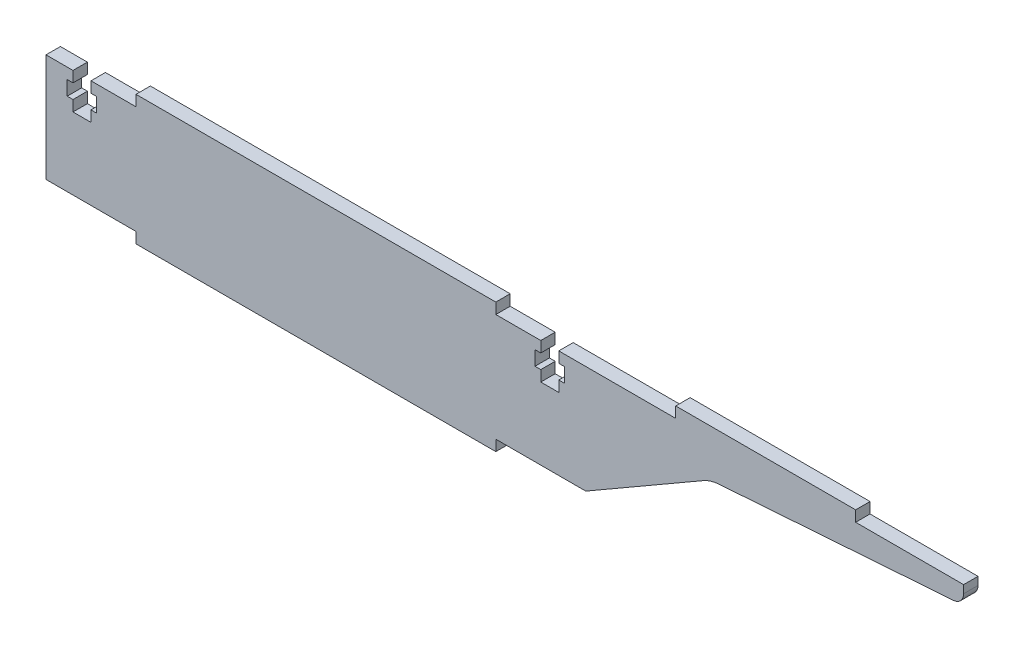
SolidWorks part; units mm, degrees
ref_plane "Front Plane" through (0, 0, 0) normal (0, 0, 1) x (1, 0, 0)
ref_plane "Top Plane" through (0, 0, 0) normal (0, 1, 0) x (1, 0, 0)
ref_plane "Right Plane" through (0, 0, 0) normal (1, 0, 0) x (0, 0, -1)
sketch "Sketch1" plane through (0, 0, 0) normal (0, 0, 1) x (1, 0, 0)
  line L1 (75, -15) -> (-75, -15)
  line L2 (75, -15) -> (75, 15)
  line L3 (75, 15) -> (-75, 15)
  line L4 (-75, -15) -> (-75, 15)
  line L5 (75, -15) -> (-75, 15) construction
  line L6 (75, 15) -> (-75, -15) construction
  line L7 (50, -18) -> (-50, -18)
  line L8 (50, -18) -> (50, -12)
  line L9 (50, -12) -> (-50, -12)
  line L10 (-50, -18) -> (-50, -12)
  line L11 (50, -18) -> (-50, -12) construction
  line L12 (50, -12) -> (-50, -18) construction
  line L13 (50, 12) -> (-50, 12)
  line L14 (50, 12) -> (50, 18)
  line L15 (50, 18) -> (-50, 18)
  line L16 (-50, 12) -> (-50, 18)
  line L17 (50, 12) -> (-50, 18) construction
  line L18 (50, 18) -> (-50, 12) construction
  point P0 (0, 0)
  point P6 (0, -15)
  point P11 (0, 15)
  dimension "D1" = 150
  dimension "D2" = 30
  dimension "D3" = 6
  dimension "D4" = 100
  dimension "D5" = 6
extrude "Boss-Extrude1" add sketch "Sketch1" along normal blind 4 contours L1 L10 L9 L8 L2 L3 L4 | L10 L7 L8 L1 | L10 L1 L8 L9 | L16 L3 L14 L15 | L16 L13 L14 L3
sketch "Sketch2" plane through (0, 0, 4) normal (0, 0, 1) x (1, 0, 0)
  line L1 (-67.5, 25) -> (-62.5, 25)
  line L2 (-67.5, 25) -> (-67.5, 5)
  line L3 (-67.5, 5) -> (-62.5, 5)
  line L4 (-62.5, 25) -> (-62.5, 5)
  line L5 (-67.5, 25) -> (-62.5, 5) construction
  line L6 (-67.5, 5) -> (-62.5, 25) construction
  line L8 (-60.9, 8) -> (-69.1, 8)
  line L9 (-60.9, 8) -> (-60.9, 12)
  line L10 (-60.9, 12) -> (-69.1, 12)
  line L11 (-69.1, 8) -> (-69.1, 12)
  line L12 (-60.9, 8) -> (-69.1, 12) construction
  line L13 (-60.9, 12) -> (-69.1, 8) construction
  point P0 (-65, 15)
  point P7 (-65, 10)
  dimension "D1" = 5
  dimension "D2" = 20
  dimension "D3" = 8.2
  dimension "D4" = 0
  dimension "D5" = 4
  dimension "D6" = 3
  dimension "D7" = 65
extrude "Cut-Extrude1" cut sketch "Sketch2" against normal blind 10 contours L4 L3 L2 L1 | L10 L11 L8 L9
mirror "Mirror1" about plane through (0, 0, 0) normal (1, 0, 0) of "Cut-Extrude1"
sketch "Sketch3" plane through (0, 0, 4) normal (0, 0, 1) x (1, 0, 0)
  line L0 (75, -15) -> (107.6468, 3.8486)
  line L1 (75, -15) -> (75, 15) construction
  line L2 (53.5141, 15) -> (155.2942, 15) construction
  line L3 (75, -15) -> (75, 15)
  line L4 (75, 15) -> (180, 15)
  line L5 (247.6295, 15) -> (292.9259, 15) construction
  line L6 (180, 15) -> (180, 12.7944)
  line L7 (177.2127, 9.8019) -> (111.9379, 5.1632)
  line L9 (100, 15) -> (150, 15)
  line L10 (100, 15) -> (100, 18)
  line L11 (100, 18) -> (150, 18)
  line L12 (150, 15) -> (150, 18)
  arc A0 (111.9379, 5.1632) -> (107.6468, 3.8486) centre (112.6468, -4.8116) ccw
  arc A1 (180, 12.7944) -> (177.2127, 9.8019) centre (177, 12.7944) cw
  point P15 (109.641, 5)
  point P22 (125, 18)
  line M27 (75, -15) -> (75, 15)
  dimension "D4" = 10
  dimension "D5" = 3
  dimension "D1" = 60
  dimension "D2" = 10
  dimension "D3" = 105
  dimension "D6" = 3
  dimension "D7" = 50
  dimension "D8" = 50
extrude "Boss-Extrude2" add sketch "Sketch3" against normal blind 4 contours A1 L6 L4 L0 A0 L7 M27 | L4 L12 L11 L10
